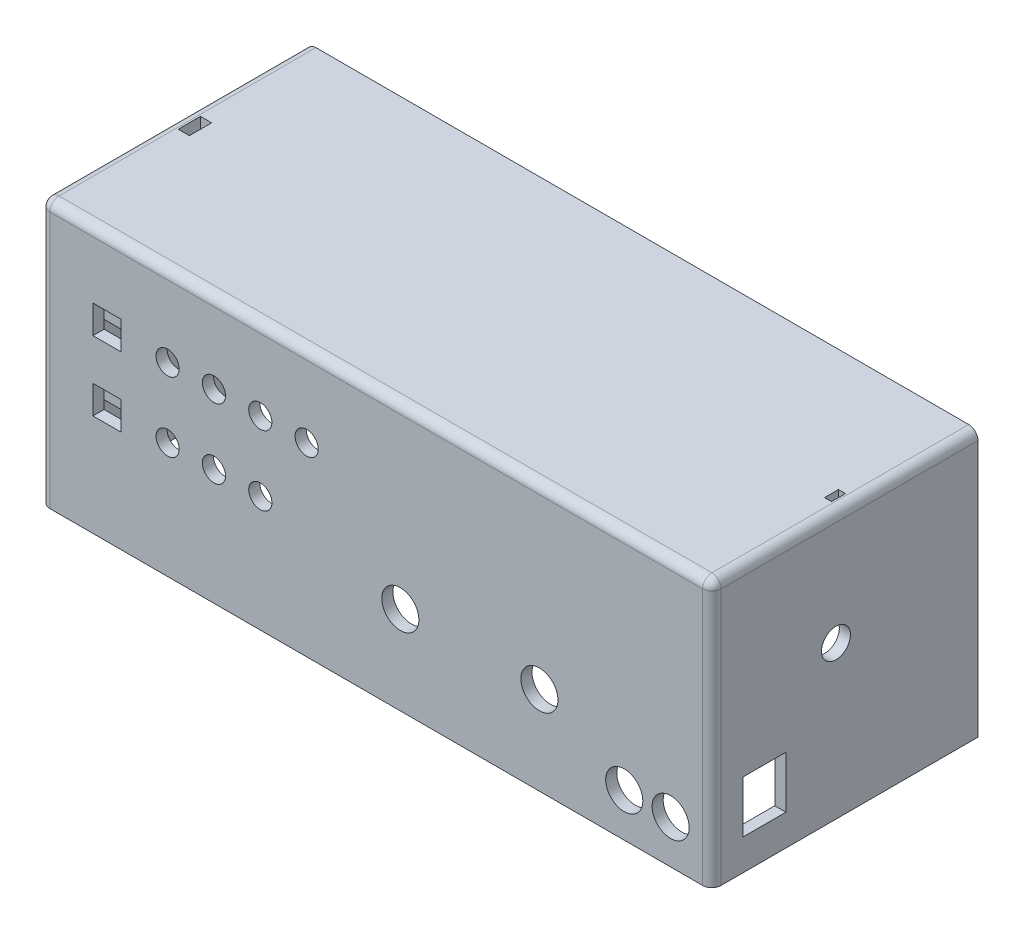
SolidWorks part; units mm, degrees
ref_plane "Front" through (0, 0, 0) normal (0, 0, 1) x (1, 0, 0)
ref_plane "Top" through (0, 0, 0) normal (0, 1, 0) x (1, 0, 0)
ref_plane "Right" through (0, 0, 0) normal (1, 0, 0) x (0, 0, -1)
sketch "Sketch2" plane through (0, 0, 0) normal (0, 1, 0) x (1, 0, 0)
  line L0 (-70, 55) -> (-70, 0)
  line L1 (-70, 0) -> (70, 0)
  line L2 (70, 0) -> (70, 55)
  line L3 (-70, 55) -> (-72.4, 55)
  line L4 (-72.4, 55) -> (-72.4, -0.4)
  line L5 (70, 55) -> (72.4, 55)
  line L6 (72.4, 55) -> (72.4, -0.4)
  line L7 (70.4, -2.4) -> (-70.4, -2.4)
  line L8 (-70, 0) -> (-70, -2.4) construction
  arc A0 (72.4, -0.4) -> (70.4, -2.4) centre (70.4, -0.4) cw
  arc A1 (-72.4, -0.4) -> (-70.4, -2.4) centre (-70.4, -0.4) ccw
  point P2 (0, 0)
  dimension "D4" = 2
  dimension "D1" = 140
  dimension "D2" = 55
  dimension "D3" = 2.4
extrude "Boss-Extrude1" add sketch "Sketch2" along normal blind 55
sketch "Sketch3" plane through (72.4, 0, 0) normal (1, 0, 0) x (0, 0, -1)
  line L0 (-0.4, 0) -> (55, 0) construction
  line L1 (4.365, 17.9) -> (13.565, 17.9)
  line L2 (4.365, 17.9) -> (4.365, 6.7)
  line L3 (4.365, 6.7) -> (13.565, 6.7)
  line L4 (13.565, 17.9) -> (13.565, 6.7)
  dimension "D1" = 11.2
  dimension "D2" = 9.2
  dimension "D3" = 6.7
extrude "Cut-Extrude1" cut sketch "Sketch3" against normal up to surface (2.4 mm away) up to face at (70, 27.5, -27.5)
sketch "Sketch4" plane through (0, 0, 2.4) normal (0, 0, 1) x (1, 0, 0)
  line L0 (-70.4, 0) -> (70.4, 0) construction
  line L1 (70, 55) -> (70, 0) construction
  circle A0 centre (53.5001, 9.325) radius 4
  circle A1 centre (35.2001, 19.025) radius 4
  dimension "D2" = 8
  dimension "D3" = 16.4999
  dimension "D4" = 8
  dimension "D1" = 9.325
  dimension "D5" = 18.3
  dimension "D6" = 9.7
extrude "Cut-Extrude2" cut sketch "Sketch4" against normal up to surface (2.4 mm away) up to face at (0, 27.5, 0)
sketch "Sketch5" plane through (0, 0, 2.4) normal (0, 0, 1) x (1, 0, 0)
  line L0 (-70.4, 0) -> (70.4, 0) construction
  line L2 (-70, 55) -> (-70, 0) construction
  circle A0 centre (-45, 25) radius 2.5
  circle A1 centre (-35, 25) radius 2.5
  circle A2 centre (-25, 25) radius 2.5
  circle A3 centre (-15, 25) radius 2.5 [skipped]
  circle A4 centre (-35, 40) radius 2.5
  circle A5 centre (-25, 40) radius 2.5
  circle A6 centre (-15, 40) radius 2.5
  circle A7 centre (-45, 40) radius 2.5
  dimension "D1" = 5
  dimension "D4" = 25
  dimension "D5" = 25
  dimension "D6" = 15
  dimension "D7" = 10
  dimension "D2" = 4
  dimension "D3" = 2
extrude "Cut-Extrude3" cut sketch "Sketch5" against normal up to surface (2.4 mm away) up to face at (57.5001, 9.325, 0)
sketch "Sketch7" plane through (0, 0, 2.4) normal (0, 0, 1) x (1, 0, 0)
  line L0 (35.2001, 19.025) -> (5.2001, 19.025) construction
  circle A0 centre (5.2001, 19.025) radius 4
  dimension "D1" = 8
  dimension "D2" = 30
extrude "Cut-Extrude4" cut sketch "Sketch7" against normal up to surface (2.4 mm away) up to face at (-32.5, 25, 0)
sketch "Sketch8" plane through (0, 0, 2.4) normal (0, 0, 1) x (1, 0, 0)
  line L0 (-45, 25) -> (-55, 25) construction
  line L1 (-61.1, 28.05) -> (-55, 28.05)
  line L2 (-61.1, 28.05) -> (-61.1, 21.95)
  line L3 (-61.1, 21.95) -> (-55, 21.95)
  line L4 (-55, 28.05) -> (-55, 21.95)
  line L5 (-61.1, 43.05) -> (-55, 43.05)
  line L6 (-61.1, 43.05) -> (-61.1, 36.95)
  line L7 (-61.1, 36.95) -> (-55, 36.95)
  line L8 (-55, 43.05) -> (-55, 36.95)
  dimension "D1" = 15
  dimension "D2" = 10
  dimension "D3" = 6.1
  dimension "D4" = 6.1
extrude "Cut-Extrude5" cut sketch "Sketch8" against normal up to surface (2.4 mm away) up to face at (9.2001, 19.025, 0)
sketch "Sketch9" plane through (0, 0, 0) normal (0, 0, -1) x (-1, 0, 0)
  line L0 (55, 36.95) -> (61.1, 36.95) construction
  line L1 (52.05, 26.2) -> (64.05, 26.2)
  line L2 (52.05, 26.2) -> (52.05, 23.8)
  line L3 (52.05, 23.8) -> (64.05, 23.8)
  line L4 (64.05, 26.2) -> (64.05, 23.8)
  line L5 (52.05, 38.8) -> (64.05, 38.8)
  line L6 (52.05, 38.8) -> (52.05, 41.2)
  line L7 (52.05, 41.2) -> (64.05, 41.2)
  line L8 (64.05, 38.8) -> (64.05, 41.2)
  line L9 (61.1, 36.95) -> (61.1, 43.05) construction
  line L10 (61.1, 21.95) -> (61.1, 28.05) construction
  line L11 (55, 21.95) -> (61.1, 21.95) construction
  point P8 (58.05, 38.8)
  point P11 (58.05, 36.95)
  point P12 (64.05, 40)
  point P15 (61.1, 40)
  point P16 (64.05, 25)
  point P19 (61.1, 25)
  point P22 (58.05, 21.95)
  point P23 (58.05, 23.8)
  dimension "D1" = 12
  dimension "D2" = 2.4
extrude "Boss-Extrude3" add sketch "Sketch9" along normal blind 2.4
sketch "Sketch10" plane through (0, 0, 2.4) normal (0, 0, 1) x (1, 0, 0)
  line L0 (63.5001, 9.325) -> (53.5001, 9.325) construction
  circle A0 centre (63.5001, 9.325) radius 4
  dimension "D1" = 8
  dimension "D2" = 10
extrude "Cut-Extrude6" cut sketch "Sketch10" against normal up to surface (2.4 mm away) up to face at (9.2001, 19.025, 0)
sketch "Sketch11" plane through (0, 55, 0) normal (0, 1, 0) x (1, 0, 0)
  line L0 (-72.4, 55) -> (72.4, 55)
  line L1 (72.4, 55) -> (72.4, -0.4)
  line L2 (70.4, -2.4) -> (-70.4, -2.4)
  line L3 (-72.4, -0.4) -> (-72.4, 55)
  line L4 (-70.4, -2.4) -> (70.4, -2.4) construction
  arc A0 (-70.4, -2.4) -> (-72.4, -0.4) centre (-70.4, -0.4) cw
  arc A1 (72.4, -0.4) -> (70.4, -2.4) centre (70.4, -0.4) cw
  dimension "D1" = 2
extrude "Boss-Extrude4" add sketch "Sketch11" along normal blind 2.4
sketch "Sketch12" plane through (0, 57.4, 0) normal (0, 1, 0) x (1, 0, 0)
  line L0 (72.4, -0.4) -> (72.4, 55) construction
  line L1 (70, 28.8) -> (68.5, 28.8)
  line L2 (70, 28.8) -> (70, 25.8)
  line L3 (70, 25.8) -> (68.5, 25.8)
  line L4 (68.5, 28.8) -> (68.5, 25.8)
  line L5 (70, 55) -> (70, 0) construction
  line L6 (-72.4, 55) -> (-72.4, -0.4) construction
  line L7 (-67.6, 29.7) -> (-70, 29.7)
  line L8 (-67.6, 29.7) -> (-67.6, 24.9)
  line L9 (-67.6, 24.9) -> (-70, 24.9)
  line L10 (-70, 29.7) -> (-70, 24.9)
  line L11 (-70, 0) -> (-70, 55) construction
  point P4 (70, 27.3)
  point P7 (72.4, 27.3)
  point P14 (-70, 27.3)
  point P17 (-72.4, 27.3)
  dimension "D1" = 1.5
  dimension "D2" = 3
  dimension "D3" = 2.4
  dimension "D4" = 4.8
extrude "Cut-Extrude7" cut sketch "Sketch12" against normal up to surface (2.4 mm away) up to face at (0, 55, -27.5)
sketch "Sketch13" plane through (72.4, 0, 0) normal (1, 0, 0) x (0, 0, -1)
  line L0 (13.565, 17.9) -> (4.365, 17.9) construction
  line L1 (4.365, 17.9) -> (4.365, 6.7) construction
  circle A0 centre (24.365, 32.9) radius 3.125
  dimension "D3" = 6.25
  dimension "D1" = 15
  dimension "D2" = 20
extrude "Cut-Extrude8" cut sketch "Sketch13" against normal up to surface (2.4 mm away) up to face at (70, 12.3, -8.965)
fillet "Fillet1" radius 2 5 edges at (-72.4, 57.4, -27.3) (-71.8142, 57.4, 1.8142) (72.4, 57.4, -27.3) (71.8142, 57.4, 1.8142) (0, 57.4, 2.4)
